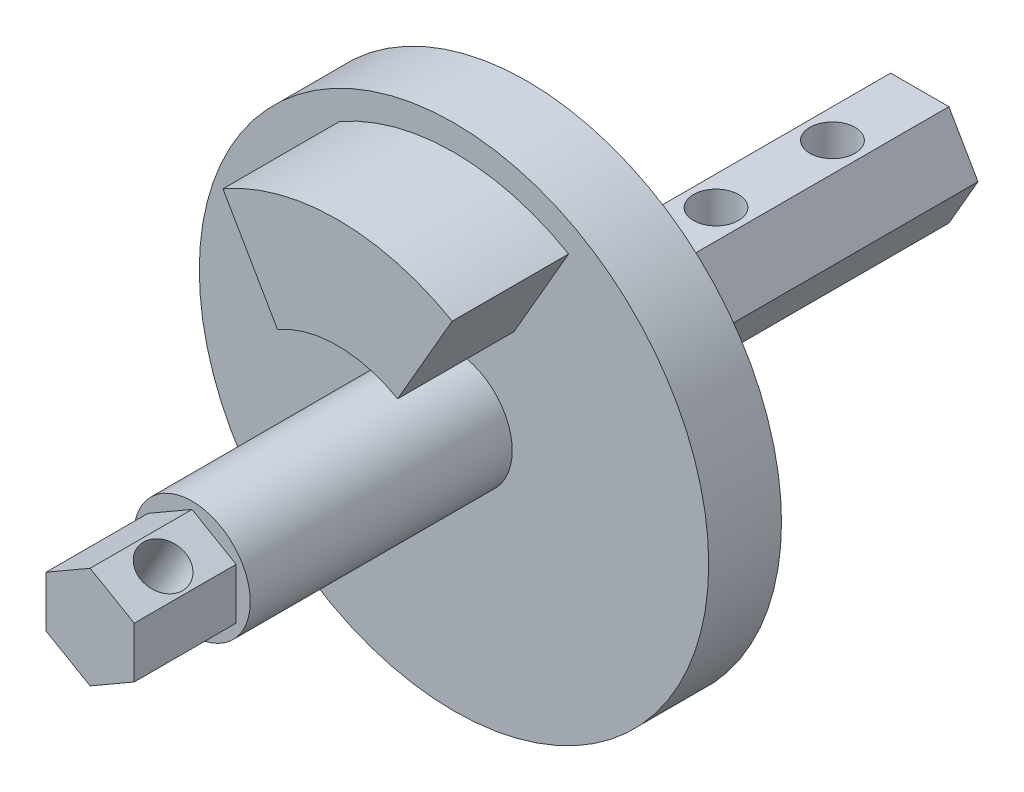
SolidWorks part; units mm, degrees
ref_plane "Front Plane" through (0, 0, 0) normal (0, 0, 1) x (1, 0, 0)
ref_plane "Top Plane" through (0, 0, 0) normal (0, 1, 0) x (1, 0, 0)
ref_plane "Right Plane" through (0, 0, 0) normal (1, 0, 0) x (0, 0, -1)
sketch "Sketch1" plane through (0, 0, 0) normal (0, 0, 1) x (1, 0, 0)
  circle A0 centre (0, 0) radius 17.5
  dimension "D1" = 35
extrude "Boss-Extrude1" add sketch "Sketch1" along normal mid plane 5
sketch "Sketch2" plane through (0, 0, 2.5) normal (0, 0, 1) x (1, 0, 0)
  line L3 (0, 0) -> (0, 11) construction
  line L4 (7.875, 13.6399) -> (4.125, 7.1447)
  line L5 (-4.125, 7.1447) -> (-7.875, 13.6399)
  arc A1 (4.125, 7.1447) -> (-4.125, 7.1447) centre (0, 0) ccw
  arc A6 (-7.875, 13.6399) -> (7.875, 13.6399) centre (0, 0) cw
  circle A7 centre (0, 0) radius 17.5 construction
  dimension "D2" = 7.5
  dimension "D3" = 1.75
  dimension "D1" = 30
extrude "Boss-Extrude2" add sketch "Sketch2" along normal blind 8
sketch "Sketch3" plane through (0, 0, 2.5) normal (0, 0, 1) x (1, 0, 0)
  circle A0 centre (0, 0) radius 4
extrude "Boss-Extrude3" add sketch "Sketch3" along normal blind 18
sketch "Sketch7" plane through (0, 0, -2.5) normal (0, 0, -1) x (-1, 0, 0)
  circle A0 centre (0, 0) radius 4
extrude "Boss-Extrude4" add sketch "Sketch7" along normal blind 7
sketch "Sketch9" plane through (0, 0, -9.5) normal (0, 0, -1) x (-1, 0, 0)
  line L0 (-4, 0) -> (4, 0) construction
  line L1 (2, -3.4641) -> (-2, 3.4641) construction
  line L2 (-2, -3.4641) -> (2, 3.4641) construction
  line L23 (4, 0) -> (2, 3.4641)
  line L24 (2, 3.4641) -> (-2, 3.4641)
  line L25 (-2, 3.4641) -> (-4, 0)
  line L26 (-4, 0) -> (-2, -3.4641)
  line L27 (-2, -3.4641) -> (2, -3.4641)
  line L28 (2, -3.4641) -> (4, 0)
  circle A1 centre (0, 0) radius 4 construction
  point P2 (0, 0)
  point P5 (0, 0)
  point P6 (0, 0)
  point P8 (0, 0)
  point P10 (0, 0)
  point P11 (0, 0)
  point P13 (0, 0)
  point P15 (0, 0)
  point P16 (0, 0)
  point P18 (0, 0)
  point P20 (0, 0)
  point P21 (0, 0)
extrude "Boss-Extrude5" add sketch "Sketch9" along normal blind 20
sketch "Sketch10" plane through (0, -3.4641, 0) normal (0, 1, 0) x (-1, 0, 0)
  line L0 (0, -9.5) -> (0, -15.5) construction
  line L1 (2, -9.5) -> (-2, -9.5) construction
  line L2 (0, -29.5) -> (0, -23.5) construction
  line L3 (2, -29.5) -> (-2, -29.5) construction
  circle A0 centre (0, -23.5) radius 1.55
  circle A1 centre (0, -15.5) radius 1.55
extrude "Cut-Extrude1" cut sketch "Sketch10" along normal blind 7
sketch "Sketch11" plane through (0, 0, 20.5) normal (0, 0, 1) x (1, 0, 0)
  line L4 (3.0311, 1.75) -> (0, 3.5)
  line L5 (0, 3.5) -> (-3.0311, 1.75)
  line L6 (-3.0311, 1.75) -> (-3.0311, -1.75)
  line L7 (-3.0311, -1.75) -> (0, -3.5)
  line L8 (0, -3.5) -> (3.0311, -1.75)
  line L9 (3.0311, -1.75) -> (3.0311, 1.75)
extrude "Boss-Extrude6" add sketch "Sketch11" along normal blind 7
sketch "Sketch12" plane through (-1.5155, -2.625, 0) normal (-0.5, -0.866, 0) x (0.866, -0.5, 0)
  circle A0 centre (0, 24) radius 1.55
extrude "Cut-Extrude2" cut sketch "Sketch12" against normal blind 6.1
